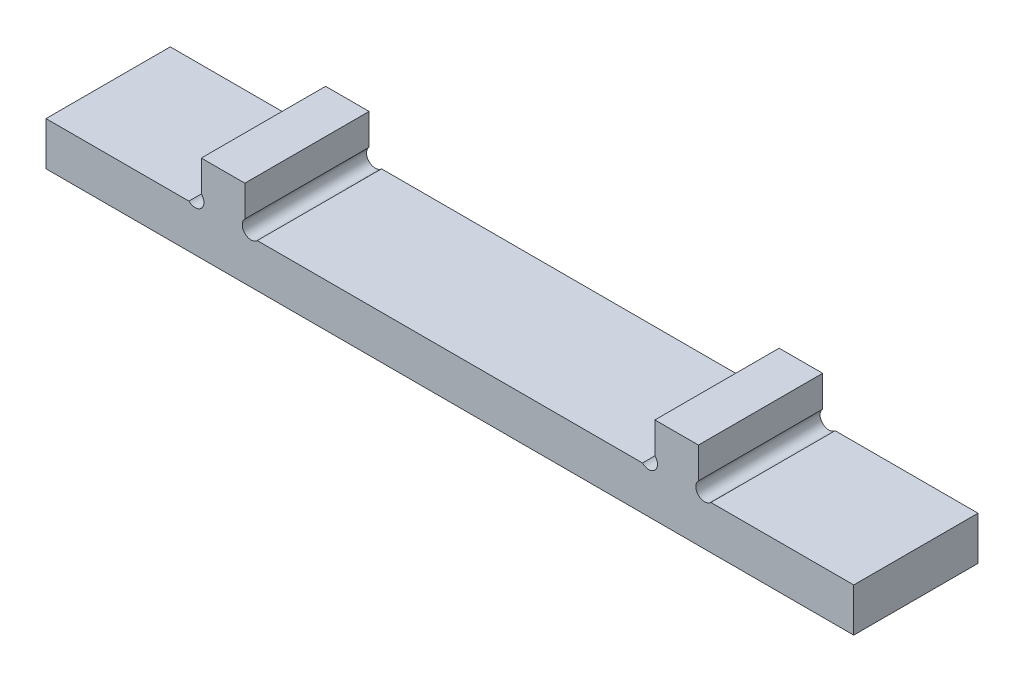
SolidWorks part; units mm, degrees
ref_plane "Front Plane" through (0, 0, 0) normal (0, 0, 1) x (1, 0, 0)
ref_plane "Top Plane" through (0, 0, 0) normal (0, 1, 0) x (1, 0, 0)
ref_plane "Right Plane" through (0, 0, 0) normal (1, 0, 0) x (0, 0, -1)
sketch "Sketch1" plane through (0, 0, 0) normal (0, 0, 1) x (1, 0, 0)
  line L0 (0, 0) -> (0, 10.0808) construction
  line L1 (-82.55, 4.445) -> (82.55, 4.445)
  line L2 (-82.55, 4.445) -> (-82.55, -4.445)
  line L3 (-82.55, -4.445) -> (82.55, -4.445)
  line L4 (82.55, 4.445) -> (82.55, -4.445)
  line L5 (-82.55, 4.445) -> (82.55, -4.445) construction
  line L6 (-82.55, -4.445) -> (82.55, 4.445) construction
  line L7 (-50.8, 4.445) -> (-41.91, 4.445)
  line L8 (-50.8, 4.445) -> (-50.8, 13.335)
  line L9 (-50.8, 13.335) -> (-41.91, 13.335)
  line L10 (-41.91, 4.445) -> (-41.91, 13.335)
  line L11 (50.8, 4.445) -> (50.8, 13.335)
  line L12 (50.8, 13.335) -> (41.91, 13.335)
  line L13 (41.91, 4.445) -> (41.91, 13.335)
  line L14 (-46.355, 13.335) -> (-46.355, 4.445) construction
  line L15 (0, 4.445) -> (0, -4.445) construction
  circle A0 centre (-40.64, 5.715) radius 1.7961
  circle A1 centre (-52.07, 5.715) radius 1.7961
  circle A2 centre (52.07, 5.715) radius 1.7961
  circle A3 centre (40.64, 5.715) radius 1.7961
  point P0 (0, 0)
  point P28 (0, 0)
  dimension "D1" = 165.1
  dimension "D2" = 8.89
  dimension "D3" = 31.75
  dimension "D4" = 8.89
  dimension "D5" = 8.89
  dimension "D6" = 101.6
  dimension "D7" = 1.27
  dimension "D8" = 1.27
extrude "Boss-Extrude1" add sketch "Sketch1" along normal blind 25.4 contours L4 L1 L2 L3 | L13 L1 L11 L12 | L1 L10 L9 L8
